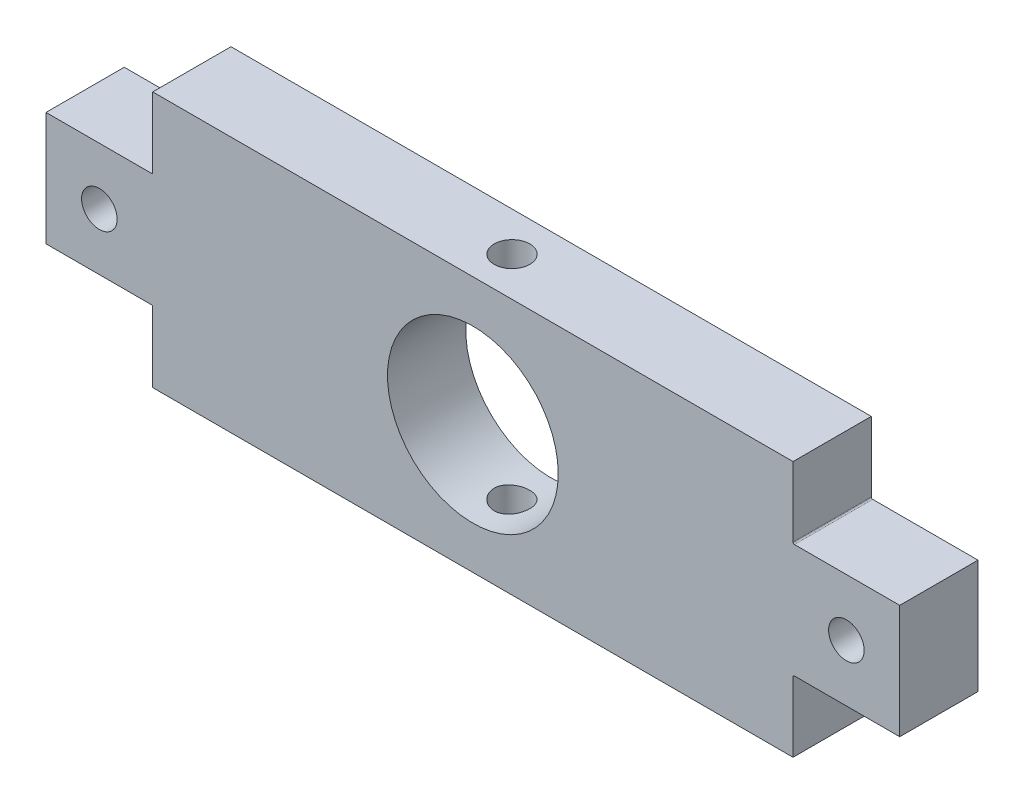
SolidWorks part; units mm, degrees
ref_plane "Piano frontale" through (0, 0, 0) normal (0, 0, 1) x (1, 0, 0)
ref_plane "Piano superiore" through (0, 0, 0) normal (0, 1, 0) x (1, 0, 0)
ref_plane "Piano destro" through (0, 0, 0) normal (1, 0, 0) x (0, 0, -1)
sketch "Schizzo2" plane through (0, 0, 0) normal (0, 0, -1) x (1, 0, 0)
  line L0 (0, 0) -> (-159.1761, 0) construction
  line L1 (0, 0) -> (0, 139.3289) construction
  line L14 (-60, -8) -> (-60, 8)
  line L15 (-60, 8) -> (-45, 8)
  line L16 (-45, 8) -> (-45, 18)
  line L17 (-45, 18) -> (45, 18)
  line L18 (45, 18) -> (45, 8)
  line L19 (45, 8) -> (60, 8)
  line L20 (60, 8) -> (60, -8)
  line L21 (60, -8) -> (45, -8)
  line L22 (45, -8) -> (45, -18)
  line L23 (45, -18) -> (-45, -18)
  line L24 (-45, -18) -> (-45, -8)
  line L25 (-45, -8) -> (-60, -8)
  dimension "D1" = 90
  dimension "D2" = 120
  dimension "D3" = 16
  dimension "D4" = 36
extrude "Estrusione-Estrusione1" add sketch "Schizzo2" against normal blind 11
sketch "Schizzo4" plane through (0, 0, 11) normal (0, 0, 1) x (1, 0, 0)
  circle A0 centre (0, 0) radius 12
  dimension "D1" = 24
extrude "Taglio-Estrusione1" cut sketch "Schizzo4" against normal through all
hole_wizard "Foro Ø5.0 (5)-1" positions "Schizzo8" profile "Schizzo9" hole size "Ø5.0" standard "ISO" end condition through all
sketch "Schizzo8" plane through (0, -18, 0) normal (0, -1, 0) x (-1, 0, 0)
  line L3 (0, 6.05) -> (0, -6.05) construction
  line L4 (-45, 0) -> (45, 0) construction
  point P0 (0, -5.5)
  dimension "D1" = 5.5
sketch "Schizzo9" plane through (0, -18, 5.5) normal (1, 0, 0) x (0, 0, -1)
  line L0 (0, 0) -> (0, 36)
  line L1 (0, 36) -> (2.5, 36)
  line L2 (2.5, 36) -> (2.5, 0)
  line L5 (2.5, 0) -> (0, 0)
  line L11 (0, -6.35) -> (0, 107.95) construction
  dimension "Thru Hole Dia." = 5
  dimension "Thru Hole Depth" = 36
hole_wizard "Foro Ø5.0 (5)-2" positions "Schizzo10" profile "Schizzo11" hole size "Ø5.0" standard "ISO" end condition through all
sketch "Schizzo10" plane through (0, 0, 11) normal (0, 0, 1) x (1, 0, 0)
  line L0 (6.05, 0) -> (-6.05, 0) construction
  line L1 (0, 0) -> (0, 41.6249) construction
  point P0 (-52.5, 0)
  point P2 (52.5, 0)
  dimension "D1" = 105
  dimension "D2" = 52.5
sketch "Schizzo11" plane through (-52.5, 0, 11) normal (1, 0, 0) x (0, -1, 0)
  line L0 (0, 0) -> (0, 11)
  line L1 (0, 11) -> (2.5, 11)
  line L2 (2.5, 11) -> (2.5, 0)
  line L5 (2.5, 0) -> (0, 0)
  line L11 (0, -6.35) -> (0, 107.95) construction
  dimension "Thru Hole Dia." = 5
  dimension "Thru Hole Depth" = 11
fillet "Raccordo1" radius 0.2 4 edges at (45, -8, 5.5) (45, 8, 5.5) (-45, 8, 5.5) (-45, -8, 5.5)
